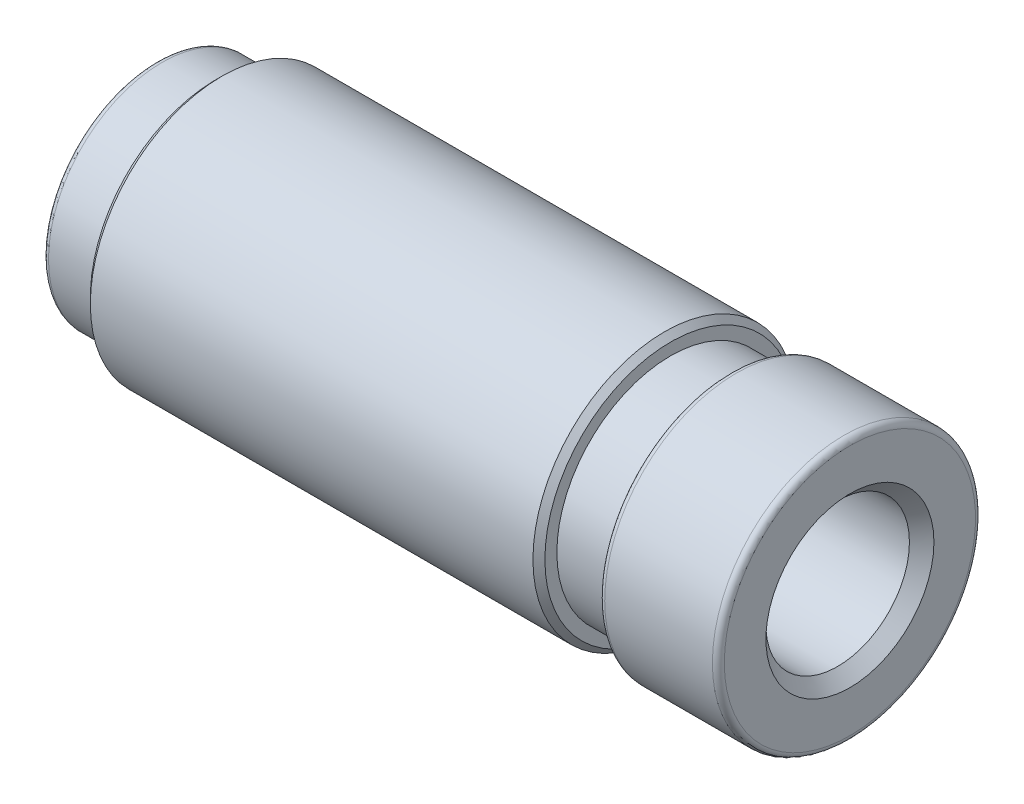
SolidWorks part; units mm, degrees
ref_plane "Plano frontal" through (0, 0, 0) normal (0, 0, 1) x (1, 0, 0)
ref_plane "Plano superior" through (0, 0, 0) normal (0, 1, 0) x (1, 0, 0)
ref_plane "Plano direito" through (0, 0, 0) normal (1, 0, 0) x (0, 0, -1)
sketch "Esboço1" plane through (0, 0, 0) normal (0, 0, 1) x (1, 0, 0)
  line L0 (0, 0) -> (58, 0)
  line L1 (58, 0) -> (58, 11)
  line L2 (58, 11) -> (48, 11)
  line L3 (48, 11) -> (48, 9.5)
  line L4 (48, 9.5) -> (43, 9.5)
  line L5 (43, 11) -> (5, 11)
  line L6 (5, 11) -> (5, 9.5)
  line L7 (5, 9.5) -> (0, 9.5)
  line L8 (0, 9.5) -> (0, 0)
  line L9 (43, 11) -> (43, 9.5)
  point P11 (45.5, 9.5)
  point P12 (2.5, 9.5)
  dimension "D1" = 10
  dimension "D2" = 5
  dimension "D3" = 5
  dimension "D4" = 38
  dimension "D5" = 11
  dimension "D6" = 1.5
  dimension "D7" = 58
revolve "Revolução1" add sketch "Esboço1" angle 360 about L0
cosmetic thread "Representação de rosca2" parameters "D1"=38, "D2"=19.252
sketch "Esboço2" plane through (0, 0, 0) normal (-1, 0, 0) x (0, 0, 1)
  circle A0 centre (0, 0) radius 7
  dimension "D1" = 14
extrude "Corte-extrusão1" cut sketch "Esboço2" against normal blind 25
hole_wizard "Furo roscado de M141" positions "Esboço3" profile "Esboço4" tap size "M14" standard "DIN"
sketch "Esboço3" plane through (58, 0, 0) normal (1, 0, 0) x (0, 0, -1)
  point P0 (0, 0)
sketch "Esboço4" plane through (58, 0, 0) normal (0, 1, 0) x (0, 0, -1)
  line L0 (0, 0) -> (0, 38.6052)
  line L1 (0, 38.6052) -> (6, 35)
  line L2 (6, 35) -> (6, 1.025)
  line L3 (6, 1.025) -> (7.025, 0)
  line L5 (7.025, 0) -> (0, 0)
  line L6 (-6, 1.025) -> (-7.025, 0) construction
  line L10 (0, 38.6052) -> (-6, 35) construction
  line L11 (0, -6.35) -> (0, 107.95) construction
  dimension "Tap Drill Dia." = 12
  dimension "Tap Drill Depth" = 35
  dimension "Near C'Sink Dia." = 14.05
  dimension "Near C'Sink Angle" = 90
  dimension "Drill Angle" = 118
cosmetic thread "Rosca de furo1"
fillet "Filete1" radius 0.5 3 edges at (58, 0, 11) (48, 0, 11) (0, 0, 9.5)
fillet "Filete2" radius 1 1 edges at (0, 0, 7)
chamfer "Chanfro1" distance 0.5 angle 45 2 edges at (43, 0, 11) (5, 0, 11)
